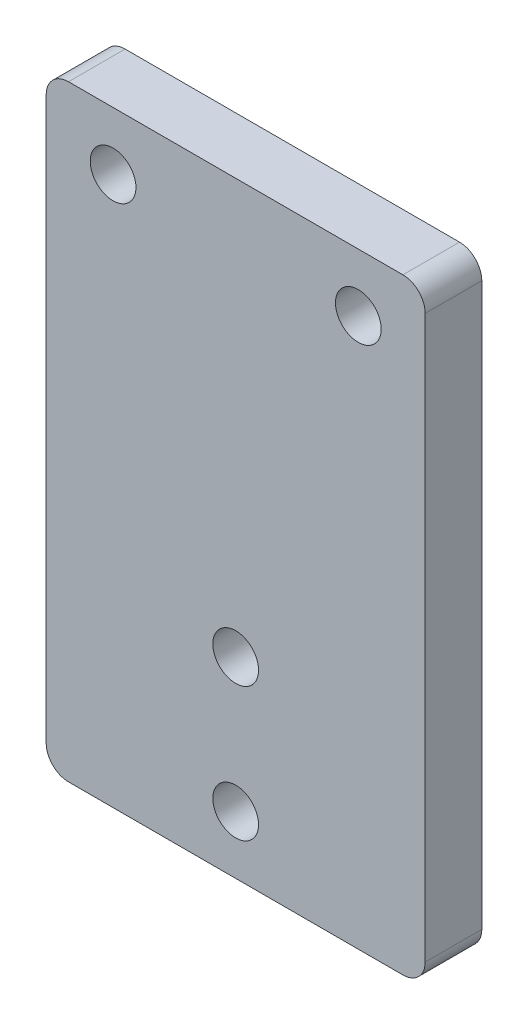
SolidWorks part; units mm, degrees
ref_plane "Alzado" through (0, 0, 0) normal (0, 0, 1) x (1, 0, 0)
ref_plane "Planta" through (0, 0, 0) normal (0, 1, 0) x (1, 0, 0)
ref_plane "Vista lateral" through (0, 0, 0) normal (1, 0, 0) x (0, 0, -1)
sketch "Croquis1" plane through (0, 0, 0) normal (0, 0, 1) x (1, 0, 0)
  line L2 (0, 0) -> (164.779, 0) construction
  line L3 (-37.5, 68) -> (37.5, 68)
  line L4 (-42.5, 63) -> (-42.5, -63)
  line L5 (-37.5, -68) -> (37.5, -68)
  line L6 (42.5, 63) -> (42.5, -63)
  line L7 (-42.5, 68) -> (42.5, -68) construction
  line L12 (-42.5, -68) -> (42.5, 68) construction
  line L13 (0, 0) -> (0, -84.2393) construction
  arc A0 (37.5, -68) -> (42.5, -63) centre (37.5, -63) ccw
  arc A1 (-42.5, -63) -> (-37.5, -68) centre (-37.5, -63) ccw
  arc A2 (37.5, 68) -> (42.5, 63) centre (37.5, 63) cw
  arc A3 (-37.5, 68) -> (-42.5, 63) centre (-37.5, 63) ccw
  circle A4 centre (-27.5, 55) radius 5.125
  circle A5 centre (27.5, 55) radius 5.125
  circle A8 centre (0, -55) radius 5.125
  circle A9 centre (0, -25) radius 5.125
  point P33 (0, 0)
  dimension "D3" = 10.25
  dimension "D21" = 5
  dimension "D22" = 27.5
  dimension "D23" = 55
  dimension "D24" = 10.25
  dimension "D4" = 55
  dimension "D5" = 10.25
  dimension "D6" = 30
  dimension "D19" = 136
  dimension "D20" = 85
extrude "Saliente-Extruir1" add sketch "Croquis1" along normal mid plane 12.7
